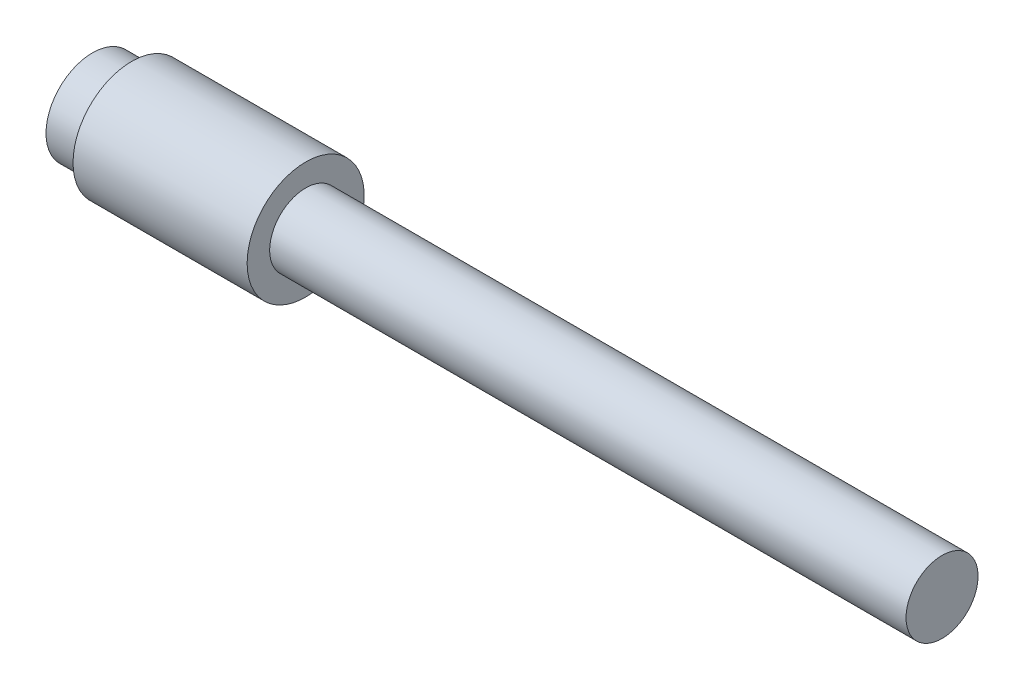
SolidWorks part; units mm, degrees
ref_plane "Plan de face" through (0, 0, 0) normal (0, 0, 1) x (1, 0, 0)
ref_plane "Plan de dessus" through (0, 0, 0) normal (0, 1, 0) x (1, 0, 0)
ref_plane "Plan de droite" through (0, 0, 0) normal (1, 0, 0) x (0, 0, -1)
sketch "Esquisse1" plane through (0, 0, 0) normal (0, 0, 1) x (1, 0, 0)
  line L0 (0, 0) -> (191.3889, 0) construction
  line L1 (0, 0) -> (0, 7.75)
  line L2 (0, 7.75) -> (6.5, 7.75)
  line L3 (6.5, 7.75) -> (6.5, 9.75)
  line L4 (6.5, 9.75) -> (35.5, 9.75)
  line L5 (35.5, 9.75) -> (35.5, 6)
  line L6 (35.5, 6) -> (141.5, 6)
  line L7 (141.5, 6) -> (141.5, 0)
  line L8 (0, 0) -> (141.5, 0)
  point P3 (6.5, 8.75)
  dimension "D1" = 6.5
  dimension "D2" = 29
  dimension "D3" = 106
  dimension "D4" = 15.5
  dimension "D5" = 2
  dimension "D6" = 12
revolve "Révolution1" add sketch "Esquisse1" angle 360 about L0
